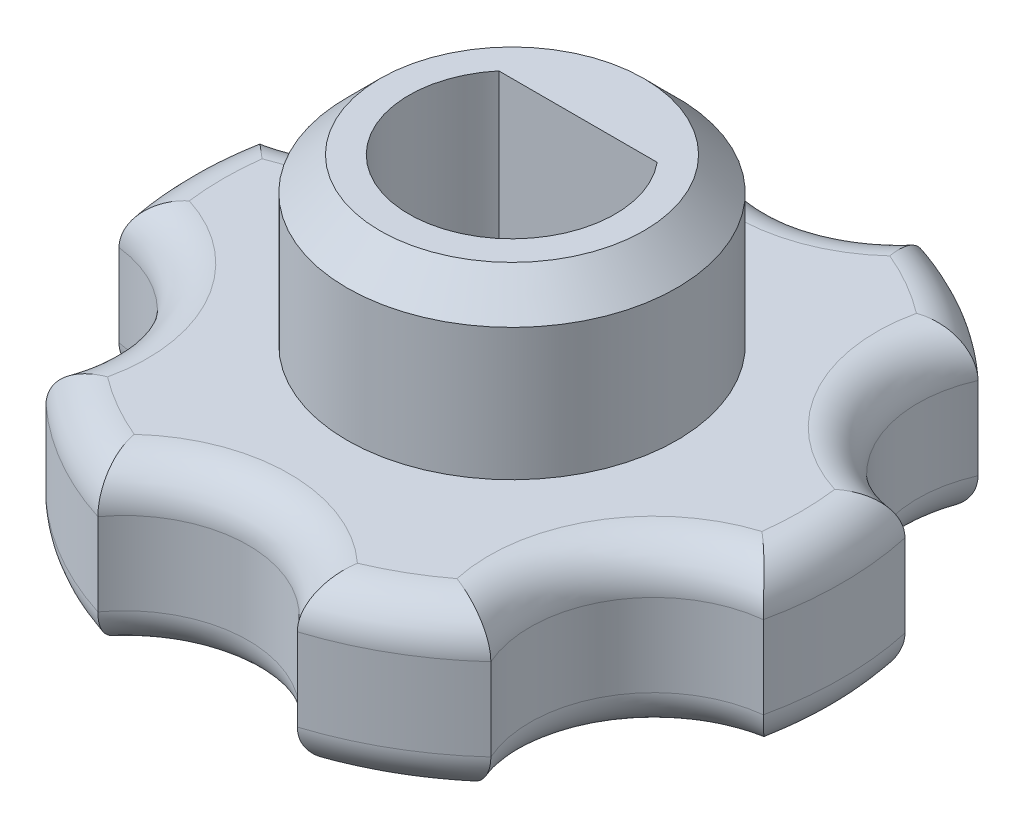
SolidWorks part; units mm, degrees
material "ABS"
ref_plane "Front Plane" through (0, 0, 0) normal (0, 0, 1) x (1, 0, 0)
ref_plane "Top Plane" through (0, 0, 0) normal (0, 1, 0) x (1, 0, 0)
ref_plane "Right Plane" through (0, 0, 0) normal (1, 0, 0) x (0, 0, -1)
sketch "Sketch3" plane through (0, 0, 0) normal (0, 1, 0) x (1, 0, 0)
  arc A0 (-39.0669, 8.5895) -> (-39.0669, -8.5895) centre (0, 0) ccw
  arc A2 (-12.0947, 38.1277) -> (12.0947, 38.1277) centre (0, 47) ccw
  arc A3 (26.9722, 29.5381) -> (39.0669, 8.5895) centre (40.7032, 23.5) ccw
  arc A4 (39.0669, -8.5895) -> (26.9722, -29.5381) centre (40.7032, -23.5) ccw
  arc A5 (12.0947, -38.1277) -> (-12.0947, -38.1277) centre (0, -47) ccw
  arc A6 (-26.9722, -29.5381) -> (-39.0669, -8.5895) centre (-40.7032, -23.5) ccw
  arc A7 (-39.0669, 8.5895) -> (-26.9722, 29.5381) centre (-40.7032, 23.5) ccw
  arc A8 (-26.9722, -29.5381) -> (-12.0947, -38.1277) centre (0, 0) ccw
  arc A9 (12.0947, -38.1277) -> (26.9722, -29.5381) centre (0, 0) ccw
  arc A10 (39.0669, -8.5895) -> (39.0669, 8.5895) centre (0, 0) ccw
  arc A11 (26.9722, 29.5381) -> (12.0947, 38.1277) centre (0, 0) ccw
  arc A12 (-12.0947, 38.1277) -> (-26.9722, 29.5381) centre (0, 0) ccw
  point P18 (0, 0)
  dimension "D1" = 80
  dimension "D2" = 12.0947
  dimension "D3" = 30
  dimension "D4" = 26.9722
extrude "Boss-Extrude1" add sketch "Sketch3" along normal blind 20
sketch "Sketch4" plane through (0, 20, 0) normal (0, 1, 0) x (1, 0, 0)
  circle A0 centre (0, 0) radius 20
  dimension "D1" = 40
extrude "Boss-Extrude2" add sketch "Sketch4" along normal blind 20
sketch "Sketch5" plane through (0, 40, 0) normal (0, 1, 0) x (1, 0, 0)
  line L0 (-9.6047, 8) -> (9.6047, 8)
  arc A0 (-9.6047, 8) -> (9.6047, 8) centre (0, 0) ccw
  dimension "D1" = 25
  dimension "D2" = 8
extrude "Cut-Extrude1" cut sketch "Sketch5" against normal up to vertex (20 mm away)
fillet "Fillet1" radius 5 24 edges at (0, 0, 32) (20, 0, 34.641) (27.7128, 0, 16) (40, 0, 0) (27.7128, 0, -16) (20, 0, -34.641) (0, 0, -32) (-20, 0, -34.641) (-20, 0, 34.641) (-27.7128, 0, 16) (-27.7128, 0, -16) (-40, 0, 0) (27.7128, 20, 16) (40, 20, 0) (27.7128, 20, -16) (20, 20, -34.641) (0, 20, -32) (-20, 20, -34.641) (-27.7128, 20, -16) (-40, 20, 0) (-27.7128, 20, 16) (20, 20, 34.641) (0, 20, 32) (-20, 20, 34.641)
chamfer "Chamfer1" distance 4 angle 45 1 edges at (0, 40, 20)
